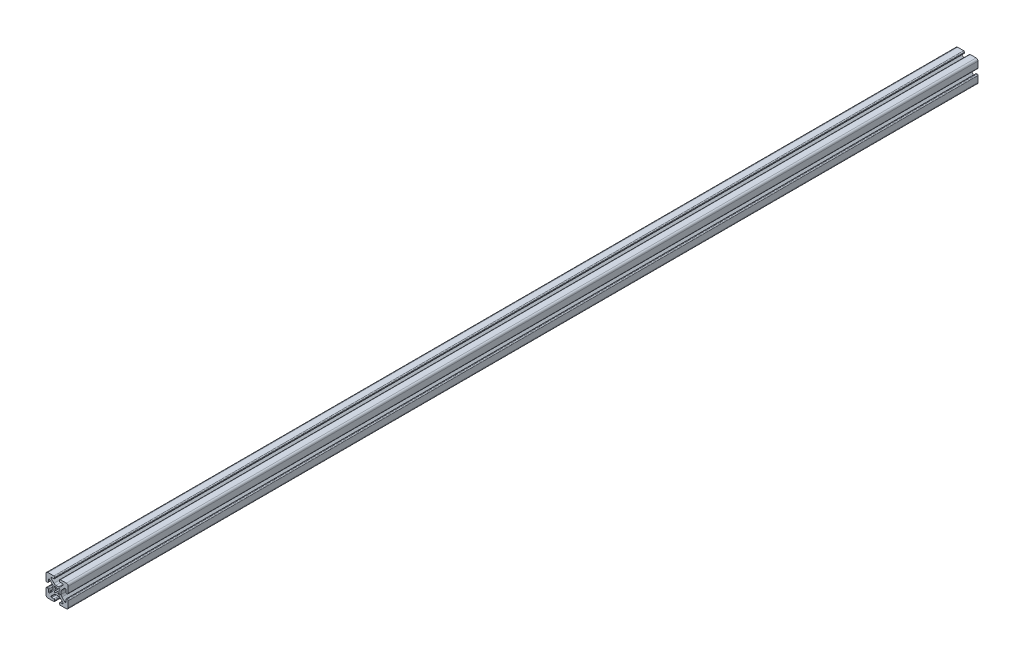
SolidWorks part; units mm, degrees
material "6105-T5 Aluminum"
ref_plane "Front Plane" through (0, 0, 0) normal (0, 0, 1) x (1, 0, 0)
ref_plane "Top Plane" through (0, 0, 0) normal (0, 1, 0) x (1, 0, 0)
ref_plane "Right Plane" through (0, 0, 0) normal (1, 0, 0) x (0, 0, -1)
sketch "Sketch1" plane through (0, 0, 0) normal (0, 0, 1) x (1, 0, 0)
  line L0 (4.2456, 2.6398) -> (3.0178, 1.4017)
  line L1 (3.0179, -1.4014) -> (4.3433, -2.7269)
  line L2 (2.7269, -4.3433) -> (1.4014, -3.0179)
  line L3 (-1.4014, -3.0179) -> (-2.7269, -4.3433)
  line L4 (-4.3433, -2.7269) -> (-3.0179, -1.4014)
  line L5 (-3.0179, 1.4014) -> (-4.3433, 2.7269)
  line L6 (-2.7269, 4.3433) -> (-1.4014, 3.0179)
  line L7 (1.4017, 3.0178) -> (2.6398, 4.2456)
  line L8 (14.986, -5.6388) -> (14.986, -9.398)
  line L9 (14.097, -10.287) -> (13.5289, -10.287)
  line L10 (12.9003, -10.0266) -> (8.2608, -5.3872)
  line L11 (6.8697, -2.0285) -> (6.8697, 2.0285)
  line L12 (8.2608, 5.3872) -> (12.9003, 10.0266)
  line L13 (13.5289, 10.287) -> (14.097, 10.287)
  line L14 (14.986, 9.398) -> (14.986, 5.6388)
  line L15 (16.5608, 4.064) -> (17.4752, 4.064)
  line L16 (19.05, 5.6388) -> (19.05, 15.875)
  line L17 (15.875, 19.05) -> (5.6388, 19.05)
  line L18 (4.064, 17.4752) -> (4.064, 16.5608)
  line L19 (5.6388, 14.986) -> (9.398, 14.986)
  line L20 (10.287, 14.097) -> (10.287, 13.5289)
  line L21 (10.0266, 12.9003) -> (5.3872, 8.2608)
  line L22 (2.0285, 6.8697) -> (-2.0285, 6.8697)
  line L23 (-5.3872, 8.2608) -> (-10.0266, 12.9003)
  line L24 (-10.287, 13.5289) -> (-10.287, 14.097)
  line L25 (-9.398, 14.986) -> (-5.6388, 14.986)
  line L26 (-4.064, 16.5608) -> (-4.064, 17.4752)
  line L27 (-5.6388, 19.05) -> (-15.875, 19.05)
  line L28 (-19.05, 15.875) -> (-19.05, 5.6388)
  line L29 (-17.4752, 4.064) -> (-16.5608, 4.064)
  line L30 (-14.986, 5.6388) -> (-14.986, 9.398)
  line L31 (-14.097, 10.287) -> (-13.5289, 10.287)
  line L32 (-12.9003, 10.0266) -> (-8.2608, 5.3872)
  line L33 (-6.8697, 2.0285) -> (-6.8697, -2.0285)
  line L34 (-8.2608, -5.3872) -> (-12.9003, -10.0266)
  line L35 (-13.5289, -10.287) -> (-14.097, -10.287)
  line L36 (-14.986, -9.398) -> (-14.986, -5.6388)
  line L37 (-16.5608, -4.064) -> (-17.4752, -4.064)
  line L38 (-19.05, -5.6388) -> (-19.05, -15.875)
  line L39 (-15.875, -19.05) -> (-5.6388, -19.05)
  line L40 (-4.064, -17.4752) -> (-4.064, -16.5608)
  line L41 (-5.6388, -14.986) -> (-9.398, -14.986)
  line L42 (-10.287, -14.097) -> (-10.287, -13.5289)
  line L43 (-10.0266, -12.9003) -> (-5.3872, -8.2608)
  line L44 (-2.0285, -6.8697) -> (2.0285, -6.8697)
  line L45 (5.3872, -8.2608) -> (10.0266, -12.9003)
  line L46 (10.287, -13.5289) -> (10.287, -14.097)
  line L47 (9.398, -14.986) -> (5.6388, -14.986)
  line L48 (4.064, -16.5608) -> (4.064, -17.4752)
  line L49 (5.6388, -19.05) -> (15.875, -19.05)
  line L50 (19.05, -15.875) -> (19.05, -5.6388)
  line L51 (17.4752, -4.064) -> (16.5608, -4.064)
  arc A0 (4.2456, 2.6398) -> (2.6398, 4.2456) centre (3.5351, 3.5351) ccw
  arc A1 (1.4017, 3.0178) -> (-1.4014, 3.0179) centre (0, 0) ccw
  arc A2 (2.7269, -4.3433) -> (4.3433, -2.7269) centre (3.5351, -3.5351) ccw
  arc A3 (-3.0179, 1.4014) -> (-3.0179, -1.4014) centre (0, 0) ccw
  arc A4 (-4.3433, -2.7269) -> (-2.7269, -4.3433) centre (-3.5351, -3.5351) ccw
  arc A5 (-1.4014, -3.0179) -> (1.4014, -3.0179) centre (0, 0) ccw
  arc A6 (-2.7269, 4.3433) -> (-4.3433, 2.7269) centre (-3.5351, 3.5351) ccw
  arc A8 (16.5608, -4.064) -> (14.986, -5.6388) centre (16.5608, -5.6388) ccw
  arc A9 (14.097, -10.287) -> (14.986, -9.398) centre (14.097, -9.398) ccw
  arc A10 (12.9003, -10.0266) -> (13.5289, -10.287) centre (13.5289, -9.398) ccw
  arc A11 (6.8697, -2.0285) -> (8.2608, -5.3872) centre (11.6195, -2.0285) ccw
  arc A12 (8.2608, 5.3872) -> (6.8697, 2.0285) centre (11.6195, 2.0285) ccw
  arc A13 (13.5289, 10.287) -> (12.9003, 10.0266) centre (13.5289, 9.398) ccw
  arc A14 (14.986, 9.398) -> (14.097, 10.287) centre (14.097, 9.398) ccw
  arc A15 (14.986, 5.6388) -> (16.5608, 4.064) centre (16.5608, 5.6388) ccw
  arc A16 (17.4752, 4.064) -> (19.05, 5.6388) centre (17.4752, 5.6388) ccw
  arc A17 (19.05, 15.875) -> (15.875, 19.05) centre (15.875, 15.875) ccw
  arc A18 (5.6388, 19.05) -> (4.064, 17.4752) centre (5.6388, 17.4752) ccw
  arc A19 (4.064, 16.5608) -> (5.6388, 14.986) centre (5.6388, 16.5608) ccw
  arc A20 (10.287, 14.097) -> (9.398, 14.986) centre (9.398, 14.097) ccw
  arc A21 (10.0266, 12.9003) -> (10.287, 13.5289) centre (9.398, 13.5289) ccw
  arc A22 (2.0285, 6.8697) -> (5.3872, 8.2608) centre (2.0285, 11.6195) ccw
  arc A23 (-5.3872, 8.2608) -> (-2.0285, 6.8697) centre (-2.0285, 11.6195) ccw
  arc A24 (-10.287, 13.5289) -> (-10.0266, 12.9003) centre (-9.398, 13.5289) ccw
  arc A25 (-9.398, 14.986) -> (-10.287, 14.097) centre (-9.398, 14.097) ccw
  arc A26 (-5.6388, 14.986) -> (-4.064, 16.5608) centre (-5.6388, 16.5608) ccw
  arc A27 (-4.064, 17.4752) -> (-5.6388, 19.05) centre (-5.6388, 17.4752) ccw
  arc A28 (-15.875, 19.05) -> (-19.05, 15.875) centre (-15.875, 15.875) ccw
  arc A29 (-19.05, 5.6388) -> (-17.4752, 4.064) centre (-17.4752, 5.6388) ccw
  arc A30 (-16.5608, 4.064) -> (-14.986, 5.6388) centre (-16.5608, 5.6388) ccw
  arc A31 (-14.097, 10.287) -> (-14.986, 9.398) centre (-14.097, 9.398) ccw
  arc A32 (-12.9003, 10.0266) -> (-13.5289, 10.287) centre (-13.5289, 9.398) ccw
  arc A33 (-6.8697, 2.0285) -> (-8.2608, 5.3872) centre (-11.6195, 2.0285) ccw
  arc A34 (-8.2608, -5.3872) -> (-6.8697, -2.0285) centre (-11.6195, -2.0285) ccw
  arc A35 (-13.5289, -10.287) -> (-12.9003, -10.0266) centre (-13.5289, -9.398) ccw
  arc A36 (-14.986, -9.398) -> (-14.097, -10.287) centre (-14.097, -9.398) ccw
  arc A37 (-14.986, -5.6388) -> (-16.5608, -4.064) centre (-16.5608, -5.6388) ccw
  arc A38 (-17.4752, -4.064) -> (-19.05, -5.6388) centre (-17.4752, -5.6388) ccw
  arc A39 (-19.05, -15.875) -> (-15.875, -19.05) centre (-15.875, -15.875) ccw
  arc A40 (-5.6388, -19.05) -> (-4.064, -17.4752) centre (-5.6388, -17.4752) ccw
  arc A41 (-4.064, -16.5608) -> (-5.6388, -14.986) centre (-5.6388, -16.5608) ccw
  arc A42 (-10.287, -14.097) -> (-9.398, -14.986) centre (-9.398, -14.097) ccw
  arc A43 (-10.0266, -12.9003) -> (-10.287, -13.5289) centre (-9.398, -13.5289) ccw
  arc A44 (-2.0285, -6.8697) -> (-5.3872, -8.2608) centre (-2.0285, -11.6195) ccw
  arc A45 (5.3872, -8.2608) -> (2.0285, -6.8697) centre (2.0285, -11.6195) ccw
  arc A46 (10.287, -13.5289) -> (10.0266, -12.9003) centre (9.398, -13.5289) ccw
  arc A47 (9.398, -14.986) -> (10.287, -14.097) centre (9.398, -14.097) ccw
  arc A48 (5.6388, -14.986) -> (4.064, -16.5608) centre (5.6388, -16.5608) ccw
  arc A49 (4.064, -17.4752) -> (5.6388, -19.05) centre (5.6388, -17.4752) ccw
  arc A50 (15.875, -19.05) -> (19.05, -15.875) centre (15.875, -15.875) ccw
  arc A51 (19.05, -5.6388) -> (17.4752, -4.064) centre (17.4752, -5.6388) ccw
  arc A52 (3.0179, -1.4014) -> (3.0178, 1.4017) centre (0, 0) ccw
  dimension "D1" = 6.6548
extrude "Extrude1" add sketch "Sketch1" against normal blind 1562.1
